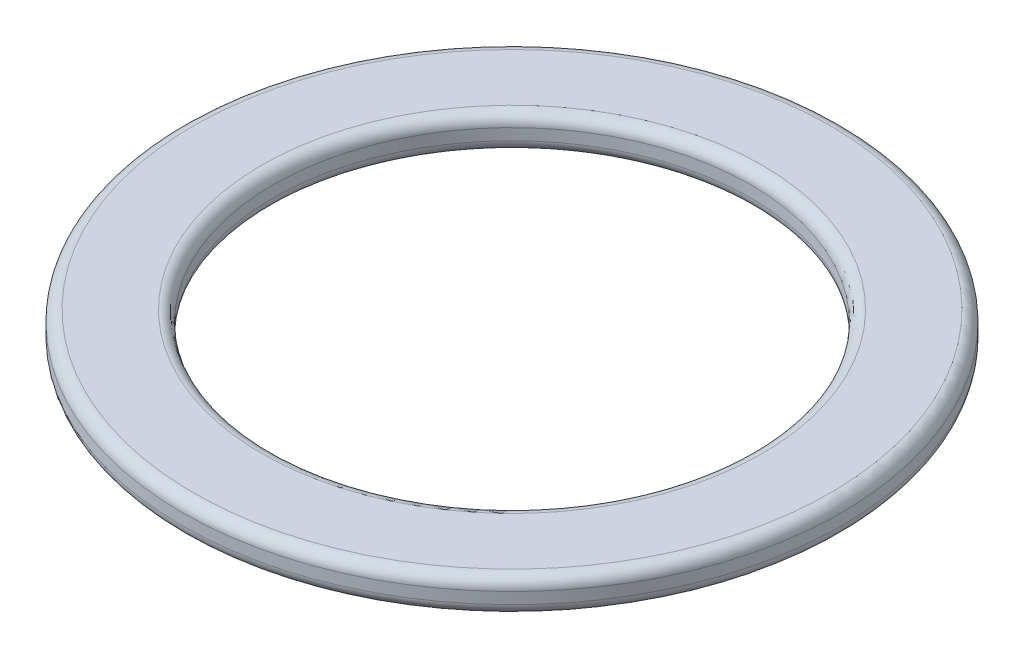
SolidWorks part; units mm, degrees
ref_plane "Front Plane" through (0, 0, 0) normal (0, 0, 1) x (1, 0, 0)
ref_plane "Top Plane" through (0, 0, 0) normal (0, 1, 0) x (1, 0, 0)
ref_plane "Right Plane" through (0, 0, 0) normal (1, 0, 0) x (0, 0, -1)
sketch "Sketch1" plane through (0, 0, 0) normal (0, 0, 1) x (1, 0, 0)
  line L0 (0, 0) -> (0, 50.7103) construction
  line L2 (-21, 3) -> (-29, 3)
  line L3 (-21, 3) -> (-21, 0)
  line L4 (-21, 0) -> (-29, 0)
  line L5 (-29, 3) -> (-29, 0)
  dimension "D1" = 42
  dimension "D2" = 58
  dimension "D3" = 3
revolve "Revolve1" add sketch "Sketch1" angle 360 about L0
fillet "Fillet1" radius 1 4 edges at (0, 0, -29) (0, 3, -29) (0, 0, -21) (0, 3, -21)
